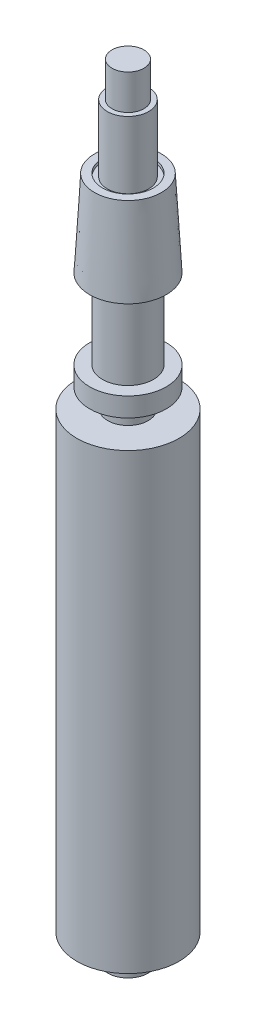
SolidWorks part; units mm, degrees
ref_plane "Ön Düzlem" through (0, 0, 0) normal (0, 0, 1) x (1, 0, 0)
ref_plane "Üst Düzlem" through (0, 0, 0) normal (0, 1, 0) x (1, 0, 0)
ref_plane "Sağ Düzlem" through (0, 0, 0) normal (1, 0, 0) x (0, 0, -1)
sketch "Çizim1" plane through (0, 0, 0) normal (0, 0, 1) x (1, 0, 0)
  line L0 (0, 0) -> (0, -274.9668) construction
  line L1 (0, 0) -> (5, 0)
  line L2 (5, 0) -> (5, -11)
  line L3 (5, -11) -> (6.5, -11)
  line L4 (6.5, -11) -> (6.5, -32)
  line L5 (6.5, -32) -> (8, -32)
  line L6 (8, -58) -> (8, -83)
  line L7 (8, -83) -> (12, -83)
  line L8 (12, -83) -> (12, -89)
  line L9 (12, -89) -> (6.3659, -89)
  line L10 (6.3659, -89) -> (6.3659, -95)
  line L11 (8, -58) -> (12, -58)
  line L12 (12, -58) -> (10.5, -31)
  line L13 (10.5, -31) -> (8, -31)
  line L14 (8, -32) -> (8, -31)
  line L15 (6.3659, -95) -> (16, -95)
  line L16 (16, -95) -> (16, -237)
  line L17 (16, -237) -> (6.3659, -237)
  line L18 (6.3659, -237) -> (6.3659, -245)
  line L19 (6.3659, -245) -> (0, -245)
  line L20 (0, 0) -> (0, -245)
  dimension "D1" = 10
  dimension "D2" = 11
  dimension "D3" = 21
  dimension "D4" = 13
  dimension "D5" = 16
  dimension "D6" = 51
  dimension "D7" = 6
  dimension "D8" = 24
  dimension "D9" = 25
  dimension "D10" = 12
  dimension "D11" = 10.5
  dimension "D12" = 20
  dimension "D13" = 162
  dimension "D14" = 16
  dimension "D15" = 8
revolve "Döndür1" add sketch "Çizim1" angle 360 about L0
